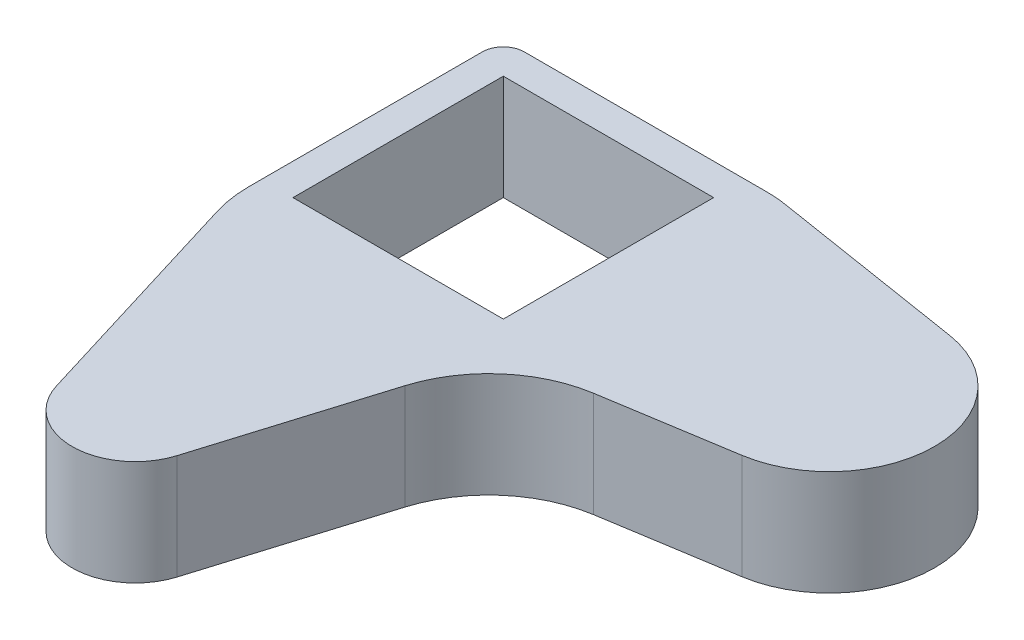
SolidWorks part; units mm, degrees
ref_plane "Front Plane" through (0, 0, 0) normal (0, 0, 1) x (1, 0, 0)
ref_plane "Top Plane" through (0, 0, 0) normal (0, 1, 0) x (1, 0, 0)
ref_plane "Right Plane" through (0, 0, 0) normal (1, 0, 0) x (0, 0, -1)
sketch "Sketch1" plane through (0, 0, 0) normal (0, 1, 0) x (1, 0, 0)
  line L0 (20, 0) -> (41, -10) construction
  line L1 (10, -45) -> (0, -20) construction
  line L2 (41, -10) -> (20, -20) construction
  line L3 (0, 0) -> (0, -20) construction
  line L4 (0, 0) -> (20, -20) construction
  line L5 (23.9399, 2.85) -> (42.5764, -0.125)
  line L12 (-3, -23) -> (23, -23) construction
  line L13 (0, 0) -> (20, 0) construction
  line L14 (0, 0) -> (0, -20) construction
  line L15 (0, -20) -> (20, -20) construction
  line L16 (20, 0) -> (20, -20) construction
  line L17 (10, -45) -> (20, -20) construction
  line L18 (-3, -21.2066) -> (-3, 1)
  line L19 (-1, 3) -> (22.0482, 3)
  line L20 (23, -23) -> (23, 3) construction
  line L21 (-3, -23) -> (23, 3) construction
  line L22 (-3, 3) -> (23, -23) construction
  line L23 (0, -20) -> (20, -20)
  line L24 (0, -20) -> (0, 0)
  line L25 (0, 0) -> (20, 0)
  line L26 (20, -20) -> (20, 0)
  line L27 (0, -20) -> (20, 0) construction
  line L28 (0, 0) -> (20, -20) construction
  line L29 (30.3947, -21.8196) -> (42.5764, -19.875)
  line L30 (20.8107, -30.1612) -> (15.7378, -46.7542)
  line L31 (-2.4757, -24.715) -> (4.2622, -46.7542)
  circle A4 centre (10, -45) radius 4 construction
  circle A5 centre (41, -10) radius 4 construction
  arc A6 (-3, 1) -> (-1, 3) centre (-1, 1) cw
  circle A7 centre (41, -10) radius 8 construction
  arc A8 (42.5764, -19.875) -> (42.5764, -0.125) centre (41, -10) ccw
  arc A9 (4.2622, -46.7542) -> (15.7378, -46.7542) centre (10, -45) ccw
  arc A10 (30.3947, -21.8196) -> (20.8107, -30.1612) centre (32.2864, -33.6695) ccw
  arc A11 (23.9399, 2.85) -> (22.0482, 3) centre (22.0482, -9) ccw
  arc A12 (-3, -21.2066) -> (-2.4757, -24.715) centre (9, -21.2066) ccw
  point P0 (10, -10)
  point P10 (10, -10)
  dimension "D6" = 8
  dimension "D7" = 16
  dimension "D8" = 20
  dimension "D9" = 12
  dimension "D10" = 12
  dimension "D11" = 12
  dimension "D5" = 2
  dimension "D2" = 20
  dimension "D3" = 3
  dimension "D4" = 45
  dimension "D12" = 20
  dimension "D13" = 41
extrude "Boss-Extrude1" add sketch "Sketch1" along normal blind 10
ref_plane "Plane1" through (0, 5, 0) normal (0, 1, 0) x (1, 0, 0)
